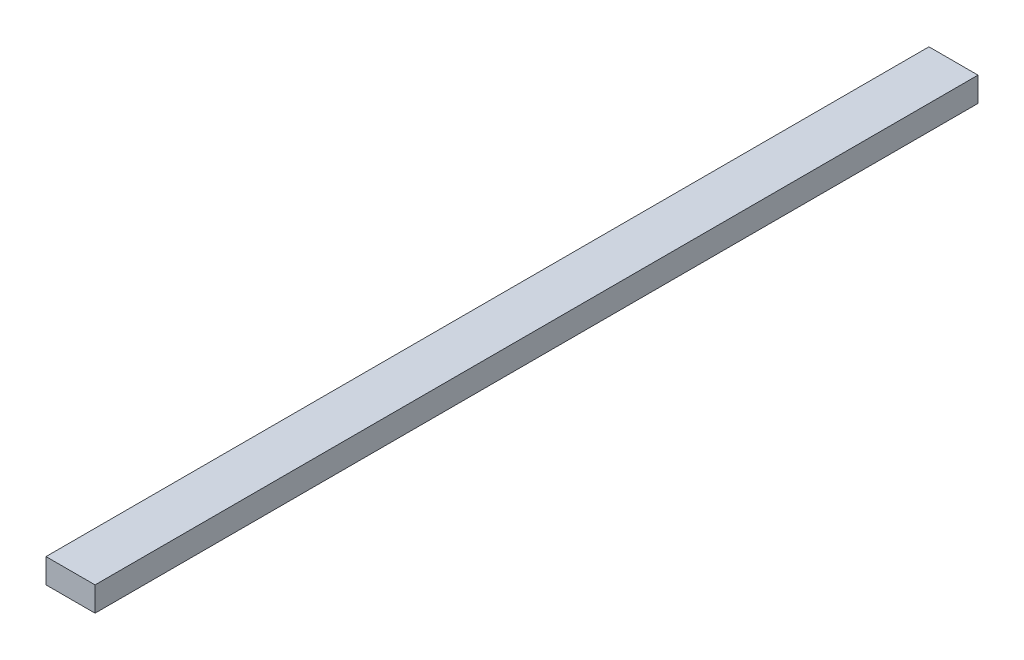
SolidWorks part; units mm, degrees
ref_plane "Front Plane" through (0, 0, 0) normal (0, 0, 1) x (1, 0, 0)
ref_plane "Top Plane" through (0, 0, 0) normal (0, 1, 0) x (1, 0, 0)
ref_plane "Right Plane" through (0, 0, 0) normal (1, 0, 0) x (0, 0, -1)
sketch "Sketch1" plane through (0, 0, 0) normal (0, 0, 1) x (1, 0, 0)
  line L1 (0, 0) -> (101.6, 0)
  line L2 (0, 0) -> (0, 50.8)
  line L3 (0, 50.8) -> (101.6, 50.8)
  line L4 (101.6, 0) -> (101.6, 50.8)
  dimension "D1" = 50.8
  dimension "D2" = 101.6
extrude "Boss-Extrude1" add sketch "Sketch1" along normal blind 1828.8
sketch "Sketch2" plane through (101.6, 0, 0) normal (1, 0, 0) x (0, 0, -1)
  line L0 (-1828.8, 50.8) -> (-965.2, 50.8) construction
  line L2 (-863.6, 50.8) -> (0, 50.8) construction
  line L3 (-863.6, 50.8) -> (-965.2, 50.8) construction
  line L4 (-1828.8, 50.8) -> (0, 50.8) construction
  line L5 (-1828.8, 0) -> (0, 0) construction
  line L6 (-965.2, 50.8) -> (-863.6, 50.8)
  line L7 (-965.2, 50.8) -> (-965.2, 0)
  line L8 (-965.2, 0) -> (-863.6, 0)
  line L9 (-863.6, 50.8) -> (-863.6, 0)
  dimension "D1" = 101.6
  dimension "D2" = 101.6
